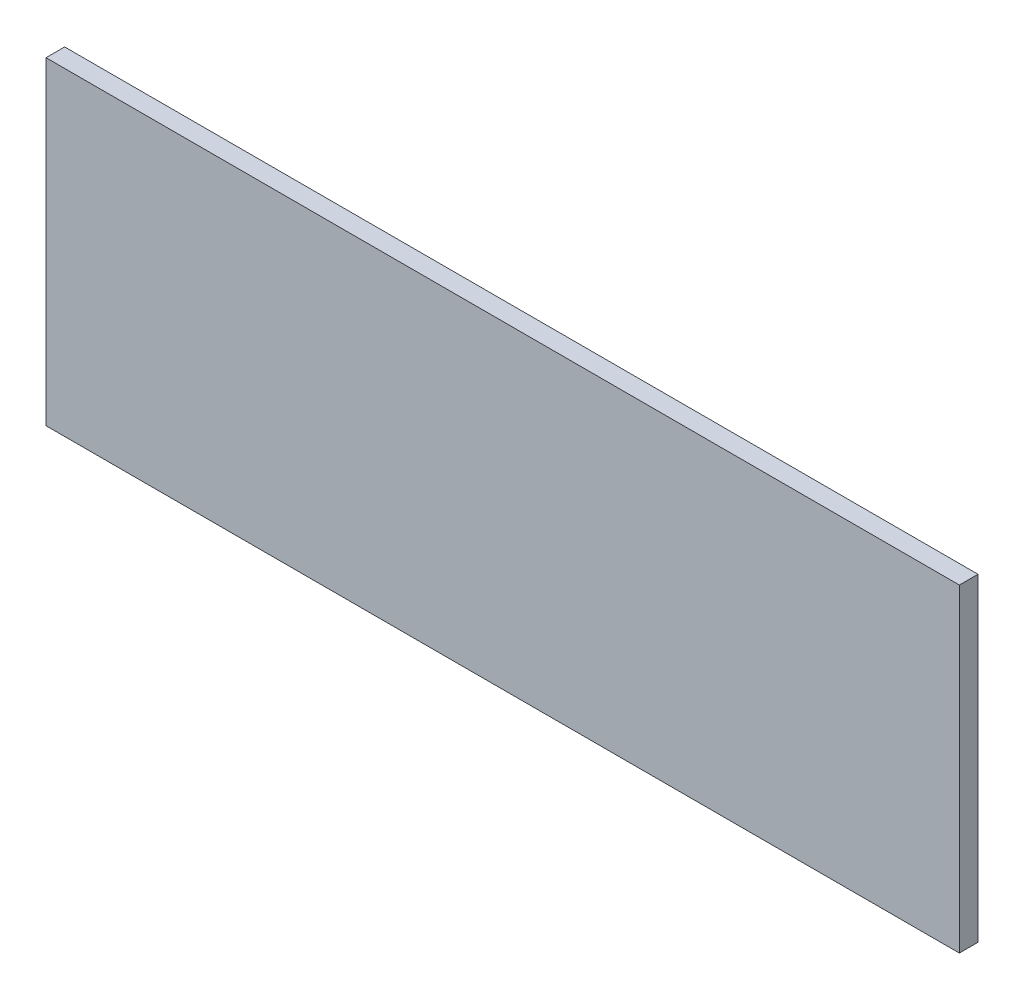
SolidWorks part; units mm, degrees
ref_plane "Alzado" through (0, 0, 0) normal (0, 0, 1) x (1, 0, 0)
ref_plane "Planta" through (0, 0, 0) normal (0, 1, 0) x (1, 0, 0)
ref_plane "Vista lateral" through (0, 0, 0) normal (1, 0, 0) x (0, 0, -1)
sketch "Croquis1" plane through (0, 0, 0) normal (0, 0, 1) x (1, 0, 0)
  line L1 (-49, -17.1) -> (49, -17.1)
  line L2 (-49, -17.1) -> (-49, 17.1)
  line L3 (-49, 17.1) -> (49, 17.1)
  line L4 (49, -17.1) -> (49, 17.1)
  point P4 (0, -17.1)
  point P6 (-49, 0)
  dimension "D1" = 98
  dimension "D2" = 34.2
extrude "Saliente-Extruir1" add sketch "Croquis1" along normal blind 2
